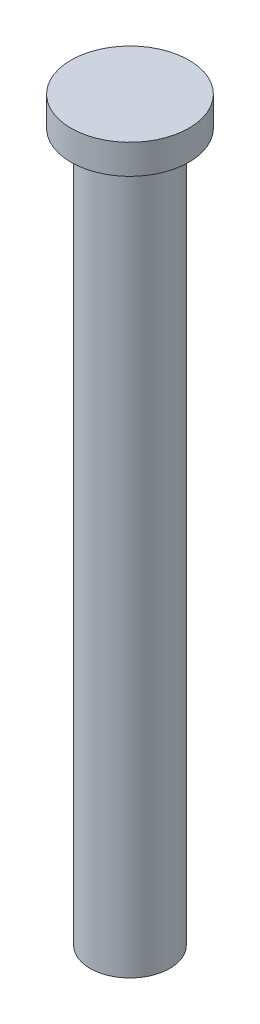
SolidWorks part; units mm, degrees
ref_plane "Front Plane" through (0, 0, 0) normal (0, 0, 1) x (1, 0, 0)
ref_plane "Top Plane" through (0, 0, 0) normal (0, 1, 0) x (1, 0, 0)
ref_plane "Right Plane" through (0, 0, 0) normal (1, 0, 0) x (0, 0, -1)
sketch "Sketch1" plane through (0, 0, 0) normal (0, 1, 0) x (1, 0, 0)
  circle A0 centre (0, 0) radius 6.75
  dimension "D1" = 13.5
extrude "Boss-Extrude1" add sketch "Sketch1" along normal blind 120
sketch "Sketch2" plane through (0, 120, 0) normal (0, 1, 0) x (1, 0, 0)
  circle A0 centre (0, 0) radius 10
  dimension "D1" = 20
extrude "Boss-Extrude2" add sketch "Sketch2" along normal blind 5
